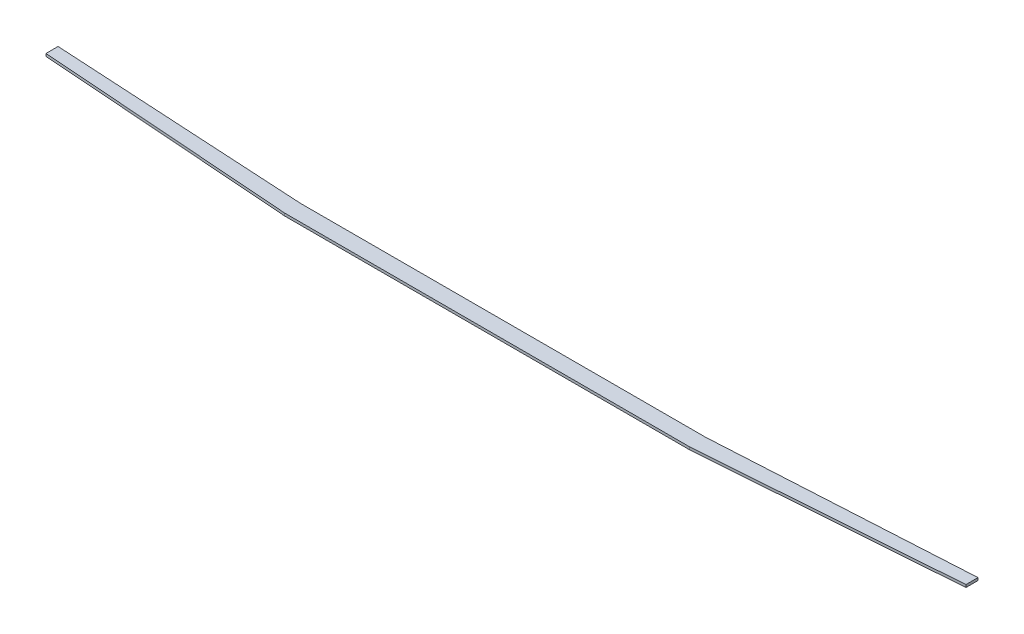
SolidWorks part; units mm, degrees
ref_plane "Front Plane" through (0, 0, 0) normal (0, 0, 1) x (1, 0, 0)
ref_plane "Top Plane" through (0, 0, 0) normal (0, 1, 0) x (1, 0, 0)
ref_plane "Right Plane" through (0, 0, 0) normal (1, 0, 0) x (0, 0, -1)
sketch "Sketch1" plane through (0, 0, 0) normal (0, 1, 0) x (1, 0, 0)
  line L0 (335.3, -13.5) -> (762, 17.8)
  line L1 (0, 13.5) -> (335.3, 13.5)
  line L2 (0, 13.5) -> (0, -13.5)
  line L3 (0, -13.5) -> (335.3, -13.5)
  line L4 (335.3, 13.5) -> (335.3, -13.5) construction
  line L5 (762, 17.8) -> (762, 37.8)
  line L6 (762, 37.8) -> (335.3, 13.5)
  point P4 (0, 0)
  dimension "D1" = 27
  dimension "D2" = 335.3
  dimension "D3" = 426.7
  dimension "D4" = 20
  dimension "D5" = 31.3
extrude "Boss-Extrude1" add sketch "Sketch1" along normal blind 4.3
mirror "Mirror1" about plane through (0, 4.3, -13.5) normal (1, 0, 0) of "Boss-Extrude1"
